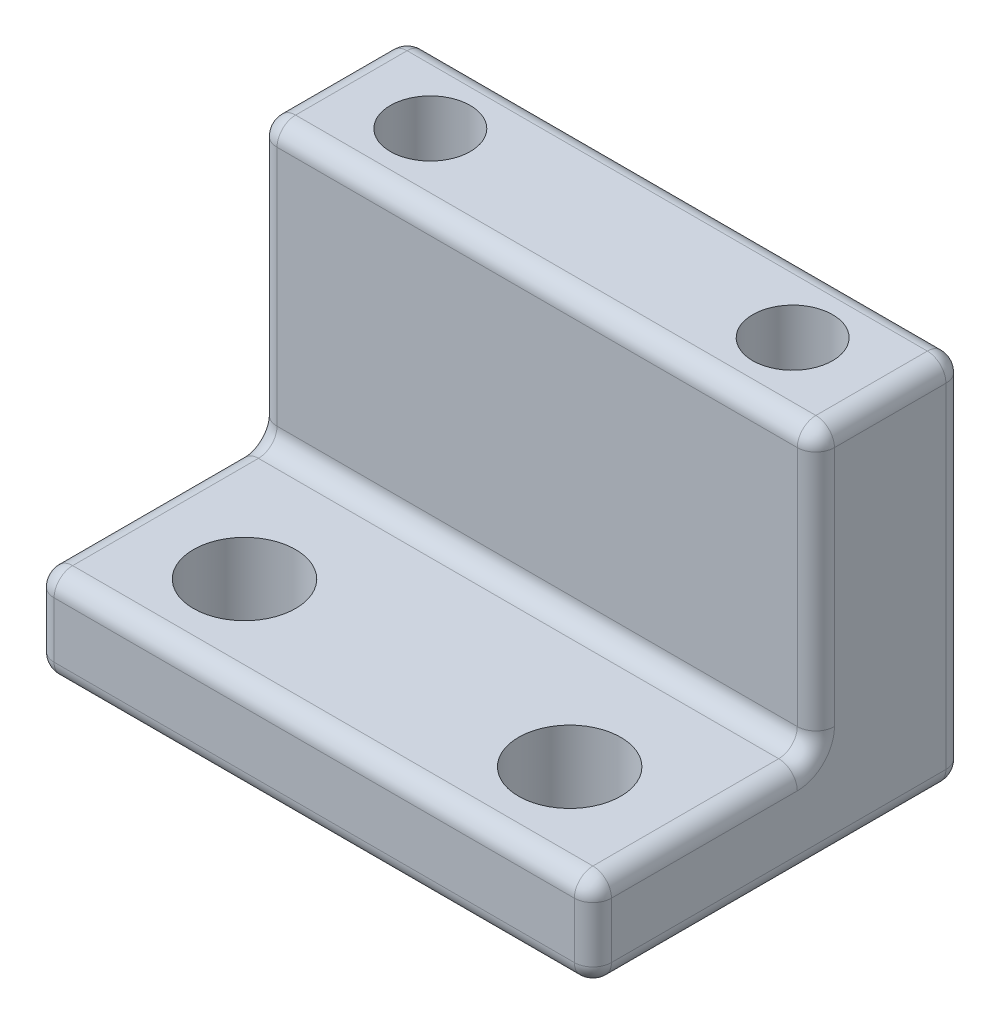
SolidWorks part; units mm, degrees
ref_plane "Front Plane" through (0, 0, 0) normal (0, 0, 1) x (1, 0, 0)
ref_plane "Top Plane" through (0, 0, 0) normal (0, 1, 0) x (1, 0, 0)
ref_plane "Right Plane" through (0, 0, 0) normal (1, 0, 0) x (0, 0, -1)
sketch "Sketch1" plane through (0, 0, 0) normal (0, 1, 0) x (1, 0, 0)
  line L0 (0, 5) -> (6.25, 5) construction
  line L1 (0, 0) -> (30, 0)
  line L2 (0, 0) -> (0, 20)
  line L3 (0, 20) -> (30, 20)
  line L4 (30, 0) -> (30, 20)
  line L5 (6.25, 5) -> (23.75, 5) construction
  line L6 (23.75, 5) -> (30, 5) construction
  circle A0 centre (6.25, 5) radius 2.75
  circle A1 centre (23.75, 5) radius 2.75
  dimension "D1" = 5.5
  dimension "D2" = 30
  dimension "D3" = 20
  dimension "D4" = 5
  dimension "D5" = 17.5
extrude "Boss-Extrude1" add sketch "Sketch1" along normal blind 5
sketch "Sketch2" plane through (0, 5, 0) normal (0, 1, 0) x (1, 0, 0)
  line L0 (30, 0) -> (30, 20) construction
  line L1 (0, 20) -> (30, 20)
  line L2 (0, 20) -> (0, 12)
  line L3 (0, 12) -> (30, 12)
  line L4 (30, 20) -> (30, 12)
  dimension "D1" = 8
extrude "Boss-Extrude2" add sketch "Sketch2" along normal blind 15
sketch "Sketch3" plane through (0, 20, 0) normal (0, 1, 0) x (1, 0, 0)
  line L0 (0, 16) -> (5.25, 16) construction
  line L1 (0, 20) -> (0, 12) construction
  line L2 (5.25, 16) -> (24.75, 16) construction
  line L3 (24.75, 16) -> (30, 16) construction
  line L4 (30, 12) -> (30, 20) construction
  circle A0 centre (5.25, 16) radius 2.15
  circle A1 centre (24.75, 16) radius 2.15
  dimension "D2" = 4.3
  dimension "D1" = 19.5
extrude "Cut-Extrude1" cut sketch "Sketch3" against normal blind 6
fillet "Fillet1" radius 1 18 edges at (15, 5, 0) (15, 0, 0) (15, 20, -12) (15, 5, -12) (15, 20, -20) (15, 0, -20) (30, 2.5, 0) (30, 5, -6) (30, 12.5, -12) (30, 20, -16) (30, 10, -20) (30, 0, -10) (0, 10, -20) (0, 20, -16) (0, 12.5, -12) (0, 5, -6) (0, 2.5, 0) (0, 0, -10)
